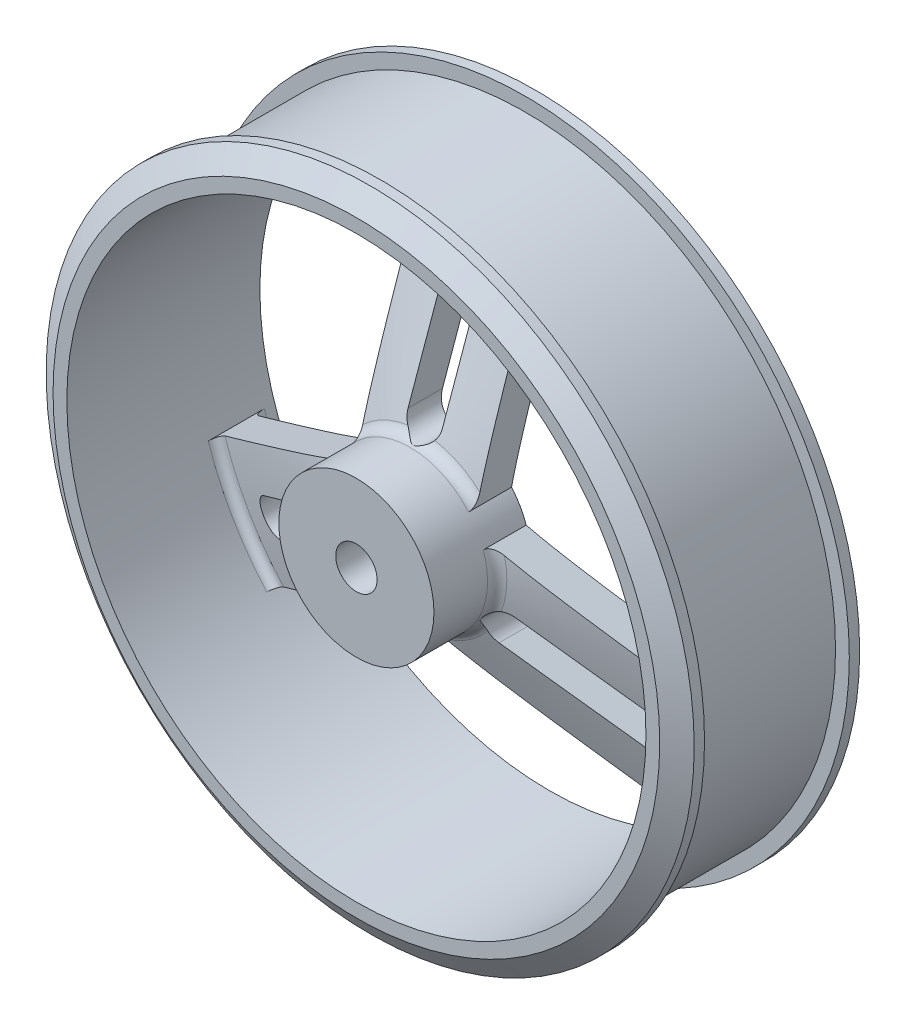
SolidWorks part; units mm, degrees
ref_plane "Front Plane" through (0, 0, 0) normal (0, 0, 1) x (1, 0, 0)
ref_plane "Top Plane" through (0, 0, 0) normal (0, 1, 0) x (1, 0, 0)
ref_plane "Right Plane" through (0, 0, 0) normal (1, 0, 0) x (0, 0, -1)
sketch "Sketch1" plane through (0, 0, 0) normal (0, 1, 0) x (1, 0, 0)
  line L0 (-80.6782, 0) -> (48.2672, 0) construction
  line L1 (0, -31.3399) -> (0, 38.3825) construction
  line L2 (-11.1746, 0) -> (-3, 0)
  line L3 (-44, 14) -> (-42, 14)
  line L4 (-47, 11.9983) -> (-47, 10.4983)
  line L5 (-44, -14) -> (-42, -14)
  line L6 (-11.25, -14) -> (-3, -14)
  line L7 (-11.25, -14) -> (-11.25, -6.2264)
  line L8 (-42, 4.3753) -> (-42, -14)
  line L9 (-40.5876, 10.4948) -> (-11.321, 0.0254)
  line L10 (-47, 10.4983) -> (-45, 10.4983)
  line L11 (-47, -10.5) -> (-45, -10.5)
  line L13 (-40.4703, 5.4528) -> (-12.4048, -4.5869)
  line L14 (-42, 14) -> (-42, 12.5)
  line L16 (-44, -14) -> (-47, -12)
  line L17 (-44, 14) -> (-47, 11.9983)
  line L18 (-47, -10.5) -> (-47, -12)
  line L19 (-45, 10.4983) -> (-45, -10.5)
  line L21 (-3, -14) -> (-3, 0)
  arc A0 (-42, 12.5) -> (-40.5876, 10.4948) centre (-39.8703, 12.5) ccw
  arc A1 (-11.1746, 0) -> (-11.321, 0.0254) centre (-11.1746, 0.4349) cw
  arc A2 (-11.25, -6.2264) -> (-12.4048, -4.5869) centre (-12.9913, -6.2264) ccw
  arc A3 (-40.4703, 5.4528) -> (-42, 4.3753) centre (-40.8557, 4.3753) ccw
  point P5 (0, 0)
  point P14 (0, -7.4193)
  dimension "D7" = 14
  dimension "D1" = 20.9983
  dimension "D2" = 28
  dimension "D3" = 2
  dimension "D4" = 47
  dimension "D5" = 3
  dimension "D6" = 11.25
  dimension "D8" = 2
  dimension "D9" = 5
  dimension "D10" = 1.5
  dimension "D11" = 3.5
revolve "Revolve2" add sketch "Sketch1" angle 360 about L1
sketch "Sketch2" plane through (0, 0, 0) normal (0, 0, 1) x (1, 0, 0)
  line L0 (0, 0) -> (0, 42) construction
  line L1 (-8.5, 41.1309) -> (-8.5, 7.3697)
  line L2 (8.5, 41.1309) -> (8.5, 7.3697)
  line L3 (2.5, 33.807) -> (2.5, 13.807)
  line L4 (-2.5, 33.807) -> (-2.5, 13.807)
  line L5 (31.3704, -27.9267) -> (2.1323, -11.0461)
  line L6 (28.0277, -19.0686) -> (10.7072, -9.0686)
  line L7 (30.5277, -14.7384) -> (13.2072, -4.7384)
  line L8 (39.8704, -13.2042) -> (10.6323, 3.6764)
  line L9 (-39.8704, -13.2042) -> (-10.6323, 3.6764)
  line L10 (-30.5277, -14.7384) -> (-13.2072, -4.7384)
  line L11 (-28.0277, -19.0686) -> (-10.7072, -9.0686)
  line L12 (-31.3704, -27.9267) -> (-2.1323, -11.0461)
  arc A0 (-8.5, 41.1309) -> (-39.8704, -13.2042) centre (0, 0) ccw
  arc A1 (-8.5, 7.3697) -> (-10.6323, 3.6764) centre (0, 0) ccw
  circle A2 centre (0, 0) radius 11.25 construction
  circle A3 centre (0, 0) radius 42 construction
  arc A4 (-2.5, 13.807) -> (2.5, 13.807) centre (0, 13.807) ccw
  arc A5 (2.5, 33.807) -> (-2.5, 33.807) centre (0, 33.807) ccw
  arc A6 (28.0277, -19.0686) -> (30.5277, -14.7384) centre (29.2777, -16.9035) ccw
  arc A7 (13.2072, -4.7384) -> (10.7072, -9.0686) centre (11.9572, -6.9035) ccw
  arc A8 (-30.5277, -14.7384) -> (-28.0277, -19.0686) centre (-29.2777, -16.9035) ccw
  arc A9 (-10.7072, -9.0686) -> (-13.2072, -4.7384) centre (-11.9572, -6.9035) ccw
  arc A10 (10.6323, 3.6764) -> (8.5, 7.3697) centre (0, 0) ccw
  arc A11 (-2.1323, -11.0461) -> (2.1323, -11.0461) centre (0, 0) ccw
  arc A12 (39.8704, -13.2042) -> (8.5, 41.1309) centre (0, 0) ccw
  arc A13 (-31.3704, -27.9267) -> (31.3704, -27.9267) centre (0, 0) ccw
  point P9 (8.5, 24.2503)
  point P42 (0, 0)
  dimension "D3" = 20
  dimension "D1" = 8.5
  dimension "D2" = 8.5
  dimension "D4" = 3
extrude "Cut-Extrude2" cut sketch "Sketch2" against normal through all both and the other way through all
